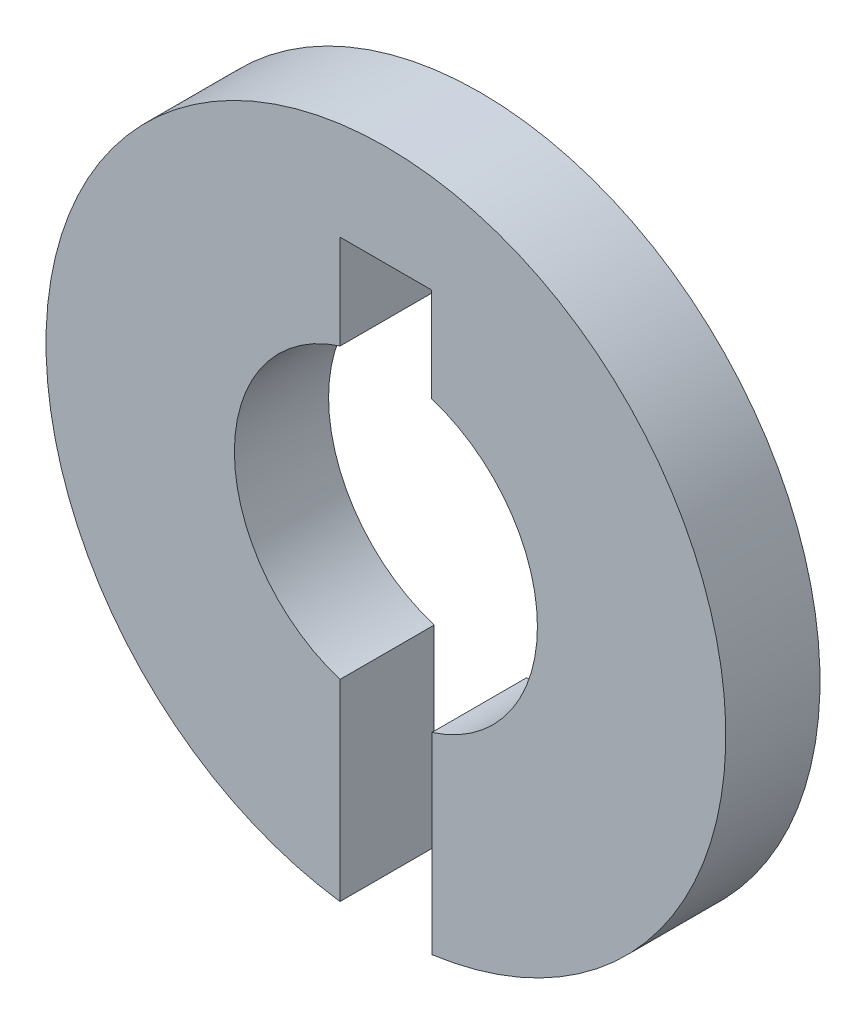
SolidWorks part; units mm, degrees
material "Acrylic (Medium-high impact)"
ref_plane "Front Plane" through (0, 0, 0) normal (0, 0, 1) x (1, 0, 0)
ref_plane "Top Plane" through (0, 0, 0) normal (0, 1, 0) x (1, 0, 0)
ref_plane "Right Plane" through (0, 0, 0) normal (1, 0, 0) x (0, 0, -1)
sketch "스케치1" plane through (0, 0, 0) normal (0, 0, 1) x (1, 0, 0)
  line L0 (0, 10.85) -> (0, 0) construction
  line L6 (-1.455, 7.6014) -> (1.455, 7.6014)
  line L7 (0, 0) -> (0, -7.6629) construction
  line L8 (-1.4625, -10.7268) -> (1.4625, -10.7268) construction
  line L9 (-1.4625, -10.7268) -> (-1.4625, -4.5991)
  line L10 (-1.4625, -4.5991) -> (1.4625, -4.5991) construction
  line L11 (1.4625, -10.7268) -> (1.4625, -4.5991)
  line L12 (-1.4625, -10.7268) -> (1.4625, -4.5991) construction
  line L13 (-1.4625, -4.5991) -> (1.4625, -10.7268) construction
  line L14 (-1.455, 7.6014) -> (-1.455, 4.6014)
  line L15 (-1.455, 4.6014) -> (1.455, 4.6014) construction
  line L16 (1.455, 7.6014) -> (1.455, 4.6014)
  line L17 (-1.455, 7.6014) -> (1.455, 4.6014) construction
  line L18 (-1.455, 4.6014) -> (1.455, 7.6014) construction
  circle A0 centre (0, 0) radius 10.826 construction
  circle A1 centre (0, 0) radius 4.826 construction
  arc A2 (-1.4625, -10.7268) -> (1.4625, -10.7268) centre (0, 0) cw
  arc A3 (1.4625, -4.5991) -> (1.455, 4.6014) centre (0, 0) ccw
  arc A4 (-1.455, 4.6014) -> (-1.4625, -4.5991) centre (0, 0) ccw
  point P2 (0, 10.85)
  point P5 (0, 6.1014)
  point P10 (0, -7.6629)
  dimension "D1" = 6
  dimension "D2" = 9.652
  dimension "D3" = 2.91
  dimension "D4" = 3
  dimension "D5" = 2.925
extrude "보스-돌출1" add sketch "스케치1" along normal blind 3
